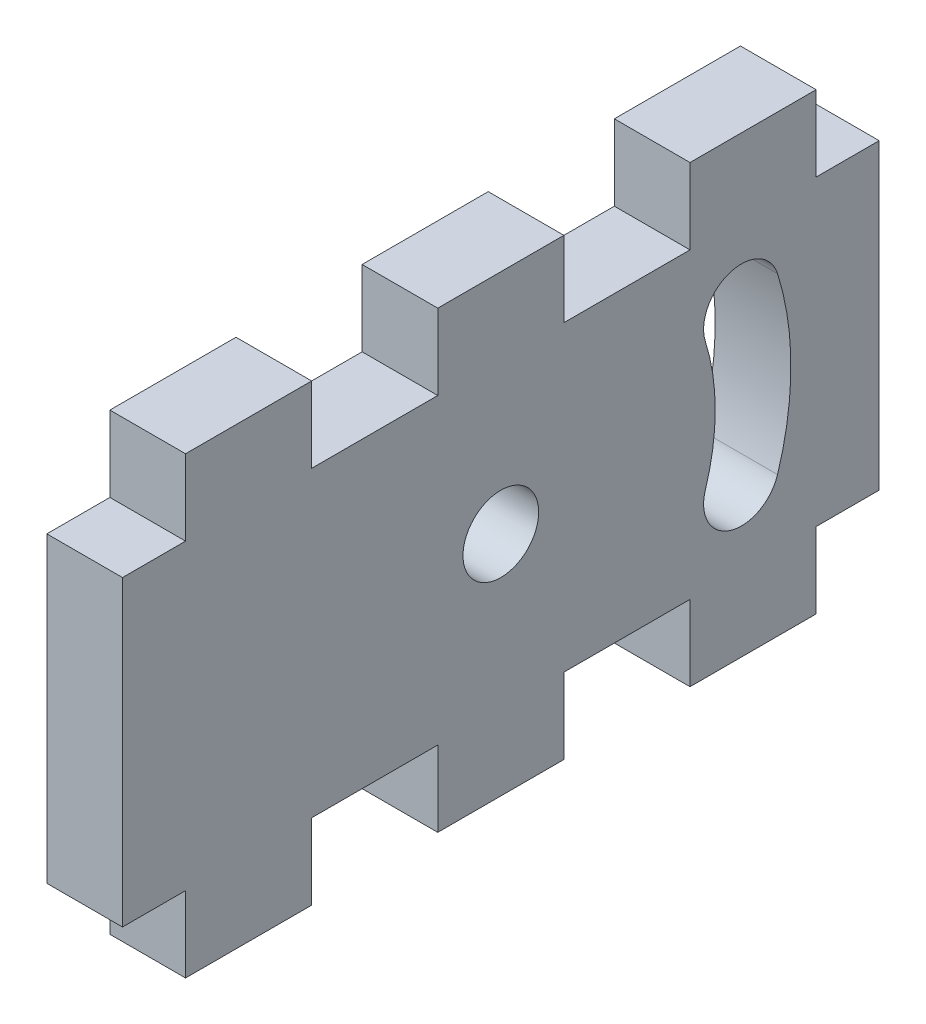
SolidWorks part; units mm, degrees
ref_plane "Front Plane" through (0, 0, 0) normal (0, 0, 1) x (1, 0, 0)
ref_plane "Top Plane" through (0, 0, 0) normal (0, 1, 0) x (1, 0, 0)
ref_plane "Right Plane" through (0, 0, 0) normal (1, 0, 0) x (0, 0, -1)
sketch "Sketch1" plane through (0, 0, 0) normal (1, 0, 0) x (0, 0, -1)
  line L1 (-15, 6) -> (15, 6)
  line L2 (-15, 6) -> (-15, -6)
  line L3 (-15, -6) -> (15, -6)
  line L4 (15, 6) -> (15, -6)
  line L5 (-15, 6) -> (15, -6) construction
  line L6 (-15, -6) -> (15, 6) construction
  point P0 (0, 0)
  dimension "D1" = 12
  dimension "D2" = 30
extrude "Boss-Extrude1" add sketch "Sketch1" along normal blind 3
sketch "Sketch3" plane through (3, 0, 0) normal (1, 0, 0) x (0, 0, -1)
  line L0 (15, 6) -> (-15, 6) construction
  line L1 (-12.5, 6) -> (-7.5, 6)
  line L2 (-12.5, 6) -> (-12.5, 9)
  line L3 (-12.5, 9) -> (-7.5, 9)
  line L4 (-7.5, 6) -> (-7.5, 9)
  line L5 (-15, 6) -> (-15, -6) construction
  line L6 (-2.5, 6) -> (2.5, 6)
  line L7 (-2.5, 6) -> (-2.5, 9)
  line L8 (-2.5, 9) -> (2.5, 9)
  line L9 (2.5, 6) -> (2.5, 9)
  line L10 (7.5, 6) -> (12.5, 6)
  line L11 (7.5, 6) -> (7.5, 9)
  line L12 (7.5, 9) -> (12.5, 9)
  line L13 (12.5, 6) -> (12.5, 9)
  line L14 (15, -6) -> (15, 6) construction
  line L15 (-18.1368, 0) -> (25.1741, 0) construction
  line L16 (12.5, -6) -> (12.5, -9)
  line L17 (7.5, -9) -> (12.5, -9)
  line L18 (7.5, -6) -> (7.5, -9)
  line L19 (7.5, -6) -> (12.5, -6)
  line L20 (2.5, -6) -> (2.5, -9)
  line L21 (-2.5, -9) -> (2.5, -9)
  line L22 (-2.5, -6) -> (-2.5, -9)
  line L23 (-2.5, -6) -> (2.5, -6)
  line L24 (-7.5, -6) -> (-7.5, -9)
  line L25 (-12.5, -9) -> (-7.5, -9)
  line L26 (-12.5, -6) -> (-12.5, -9)
  line L27 (-12.5, -6) -> (-7.5, -6)
  point P16 (-10, 9)
  point P17 (10, 9)
  point P19 (0, 9)
  dimension "D1" = 3
  dimension "D2" = 3
  dimension "D3" = 3
  dimension "D4" = 5
  dimension "D5" = 5
  dimension "D6" = 5
  dimension "D7" = 5
  dimension "D8" = 5
  dimension "D9" = 15
extrude "Boss-Extrude2" add sketch "Sketch3" against normal blind 3
sketch "Sketch4" plane through (3, 0, 0) normal (1, 0, 0) x (0, 0, -1)
  line L0 (-16.1643, 0) -> (22.3204, 0) construction
  circle A0 centre (0, 0) radius 1.5
  arc A1 (9.5394, -3) -> (9.5394, 3) centre (0, 0) ccw construction
  arc A2 (10.9703, -3.45) -> (10.9703, 3.45) centre (0, 0) ccw
  arc A3 (8.1085, -2.55) -> (8.1085, 2.55) centre (0, 0) ccw
  arc A4 (8.1085, -2.55) -> (10.9703, -3.45) centre (9.5394, -3) ccw
  arc A5 (10.9703, 3.45) -> (8.1085, 2.55) centre (9.5394, 3) ccw
  point P7 (10, 0)
  dimension "D1" = 3
  dimension "D2" = 3
  dimension "D3" = 10
  dimension "D4" = 6
extrude "Cut-Extrude1" cut sketch "Sketch4" against normal blind 10
